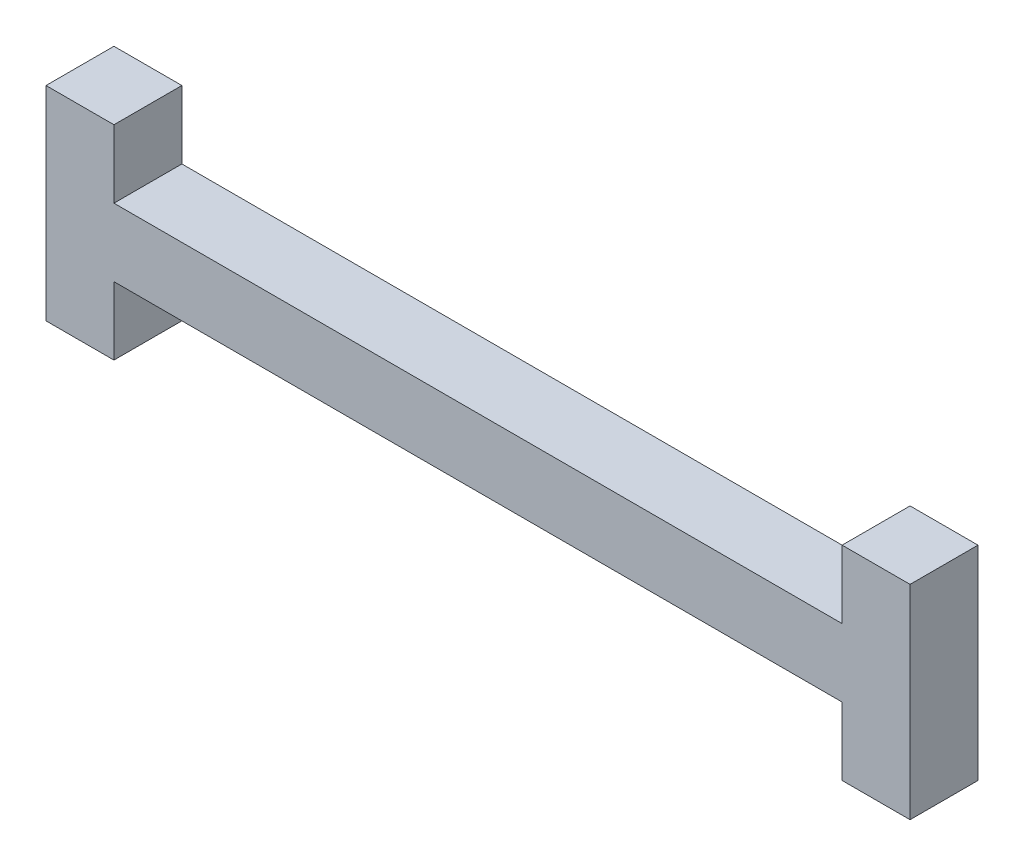
SolidWorks part; units mm, degrees
material "ABS"
ref_plane "Front Plane" through (0, 0, 0) normal (0, 0, 1) x (1, 0, 0)
ref_plane "Top Plane" through (0, 0, 0) normal (0, 1, 0) x (1, 0, 0)
ref_plane "Right Plane" through (0, 0, 0) normal (1, 0, 0) x (0, 0, -1)
sketch "Sketch1" plane through (0, 0, 0) normal (0, 0, 1) x (1, 0, 0)
  line L0 (0, 0) -> (0, -15)
  line L1 (0, -15) -> (5, -15)
  line L2 (5, -15) -> (5, -10)
  line L3 (5, -10) -> (58.585, -10)
  line L4 (58.585, -10) -> (58.585, -15)
  line L5 (58.585, -15) -> (63.585, -15)
  line L6 (63.585, -15) -> (63.585, 0)
  line L7 (63.585, 0) -> (58.585, 0)
  line L8 (58.585, 0) -> (58.585, -5)
  line L9 (58.585, -5) -> (5, -5)
  line L10 (5, -5) -> (5, 0)
  line L11 (5, 0) -> (0, 0)
  dimension "D1" = 53.585
  dimension "D2" = 15
  dimension "D3" = 5
  dimension "D4" = 5
  dimension "D5" = 5
  dimension "D6" = 5
  dimension "D7" = 5
  dimension "D8" = 5
  dimension "D9" = 53.585
extrude "Boss-Extrude1" add sketch "Sketch1" along normal blind 5
